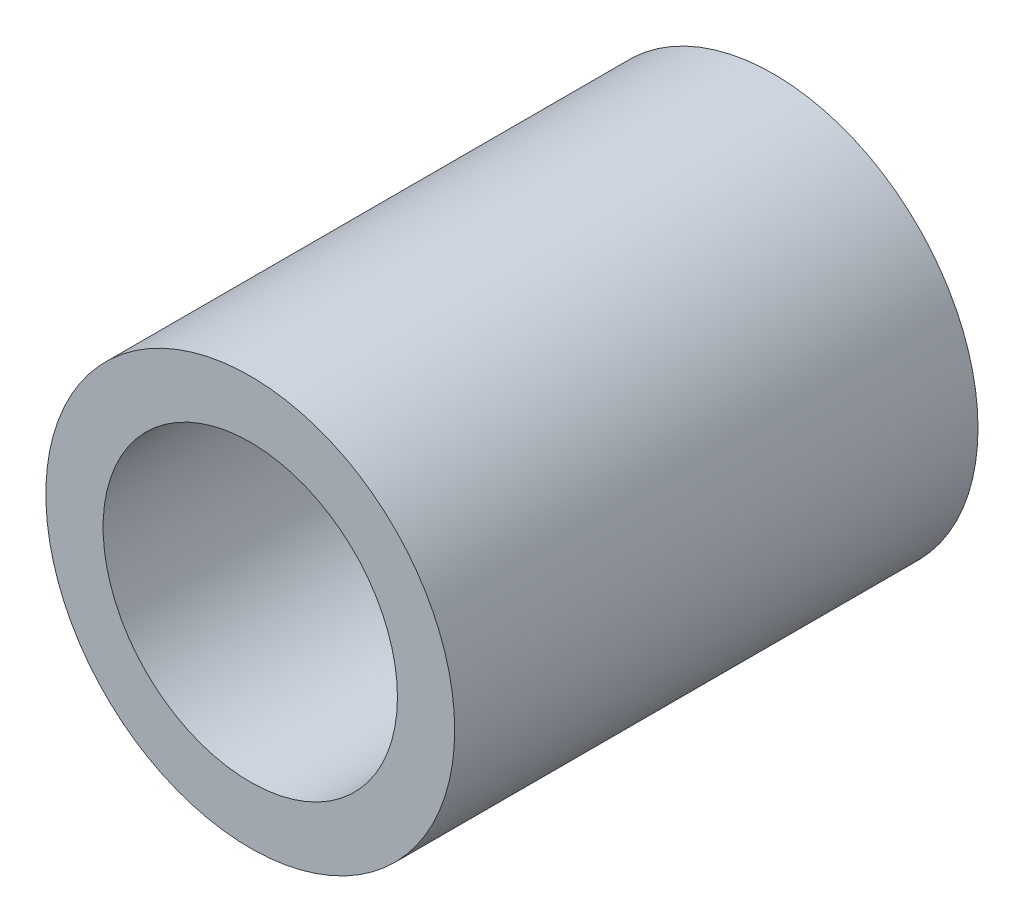
SolidWorks part; units mm, degrees
ref_plane "Front Plane" through (0, 0, 0) normal (0, 0, 1) x (1, 0, 0)
ref_plane "Top Plane" through (0, 0, 0) normal (0, 1, 0) x (1, 0, 0)
ref_plane "Right Plane" through (0, 0, 0) normal (1, 0, 0) x (0, 0, -1)
sketch "Sketch1" plane through (0, 0, 0) normal (0, 0, 1) x (1, 0, 0)
  circle A0 centre (0, 0) radius 12.5
  circle A1 centre (0, 0) radius 9
  dimension "D1" = 25
  dimension "D2" = 18
extrude "Boss-Extrude1" add sketch "Sketch1" along normal mid plane 32
